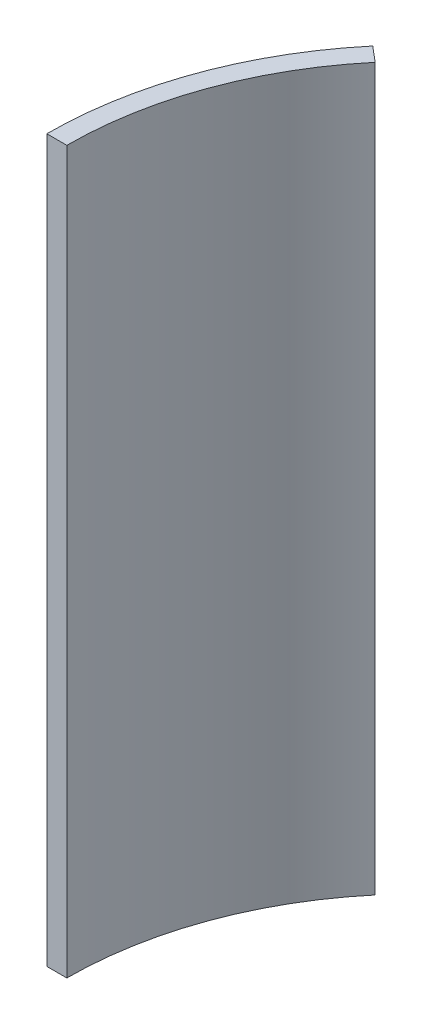
SolidWorks part; units mm, degrees
material "Custom Plastic"
ref_plane "Front Plane" through (0, 0, 0) normal (0, 0, 1) x (1, 0, 0)
ref_plane "Top Plane" through (0, 0, 0) normal (0, 1, 0) x (1, 0, 0)
ref_plane "Right Plane" through (0, 0, 0) normal (1, 0, 0) x (0, 0, -1)
sketch "Sketch1" plane through (0, 0, 0) normal (0, 1, 0) x (1, 0, 0)
  line L0 (0, 0) -> (65.2704, 0) construction
  line L1 (65.2704, 0) -> (65.2704, 50) construction
  line L2 (0, 0) -> (0, -10) construction
  line L3 (18.1985, 50) -> (-23.7565, 0) construction
  line L4 (10, 0) -> (-10, 0)
  line L5 (25.859, 43.5721) -> (10.5381, 56.4279)
  arc A0 (0, 0) -> (18.1985, 50) centre (77.7862, 0) cw construction
  arc A1 (10, 0) -> (25.859, 43.5721) centre (77.7862, 0) cw
  arc A2 (-10, 0) -> (10.5381, 56.4279) centre (77.7862, 0) cw
  circle A3 centre (0.6455, 10) radius 2.6
  circle A4 centre (4.6911, 26.6044) radius 2.6
  circle A5 centre (12.2651, 41.9247) radius 2.6
  circle A7 centre (23.0019, 55.2211) radius 2.6 [skipped]
  point P24 (77.7862, 0)
  dimension "D6" = 5.2
  dimension "D9" = 10
  dimension "D1" = 10
  dimension "D2" = 50
  dimension "D3" = 50
  dimension "D7" = 10
  dimension "D8" = 4
  dimension "D4" = 10
  dimension "D5" = 10
extrude "Boss-Extrude1" add sketch "Sketch1" along normal blind 20
sketch "Sketch2" plane through (0, 20, 0) normal (0, 1, 0) x (1, 0, 0)
  line L0 (6.7078, 59.6418) -> (10.5381, 56.4279)
  line L1 (-15, 0) -> (-10, 0)
  arc A1 (10.5381, 56.4279) -> (-10, 0) centre (77.7862, 0) ccw construction
  arc A2 (6.7078, 59.6418) -> (-15, 0) centre (77.7862, 0) ccw
  arc A3 (6.7078, 59.6418) -> (-15, 0) centre (77.7862, 0) ccw
  arc A4 (10.5381, 56.4279) -> (-10, 0) centre (77.7862, 0) ccw
  dimension "D1" = 5
extrude "Boss-Extrude2" add sketch "Sketch2" along normal blind 180 separate body
sketch "Sketch3" plane through (0, 20, 0) normal (0, 1, 0) x (1, 0, 0)
  line L2 (25.859, 43.5721) -> (10.5381, 56.4279)
  line L3 (-10, 0) -> (10, 0)
  line L4 (25.859, 43.5721) -> (10.5381, 56.4279)
  line L5 (-10, 0) -> (10, 0)
  arc A2 (25.859, 43.5721) -> (10, 0) centre (77.7862, 0) ccw
  arc A3 (10.5381, 56.4279) -> (-10, 0) centre (77.7862, 0) ccw
  arc A4 (25.859, 43.5721) -> (10, 0) centre (77.7862, 0) ccw
  arc A5 (10.5381, 56.4279) -> (-10, 0) centre (77.7862, 0) ccw
  dimension "D1" = 0
extrude "Cut-Extrude1" cut sketch "Sketch3" against normal through all
